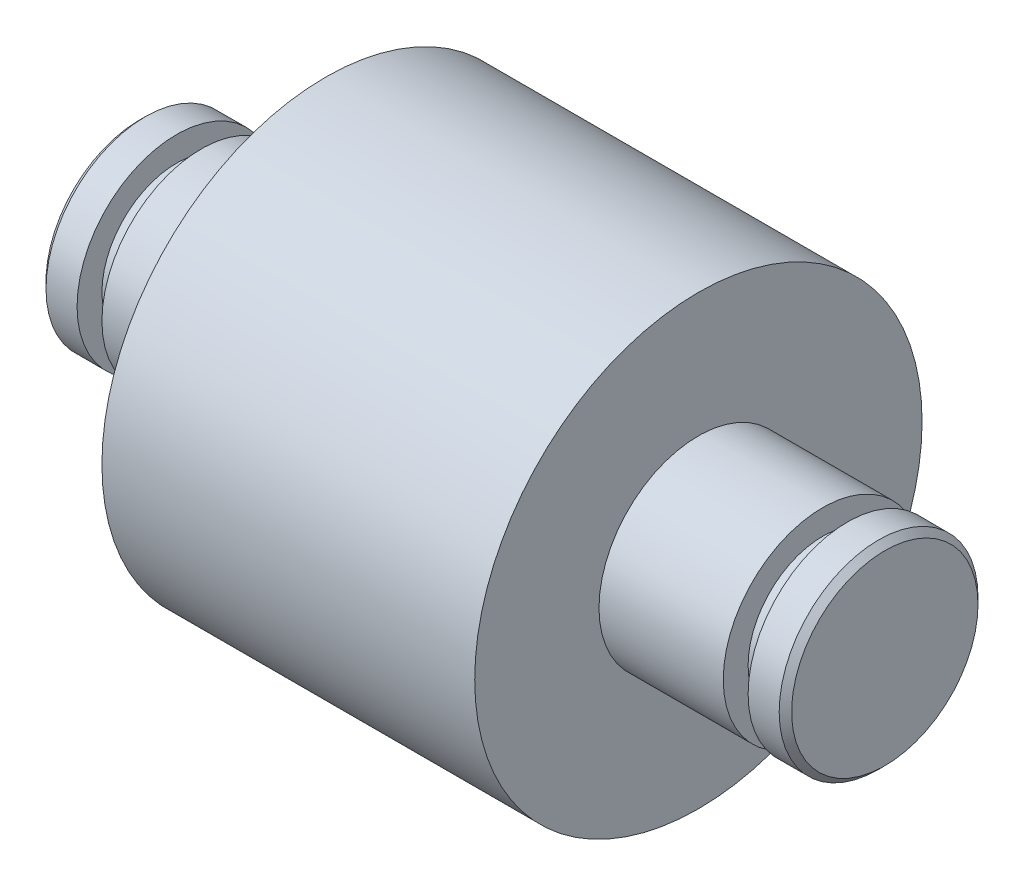
SolidWorks part; units mm, degrees
ref_plane "Front Plane" through (0, 0, 0) normal (0, 0, 1) x (1, 0, 0)
ref_plane "Top Plane" through (0, 0, 0) normal (0, 1, 0) x (1, 0, 0)
ref_plane "Right Plane" through (0, 0, 0) normal (1, 0, 0) x (0, 0, -1)
sketch "Sketch1" plane through (0, 0, 0) normal (0, 0, 1) x (1, 0, 0)
  line L0 (1000, 0) -> (15, 0) construction
  line L1 (0, -1000) -> (0, -9) construction
  line L2 (-15, 0) -> (15, 0)
  line L5 (-7.5, 9) -> (7.5, 9)
  line L7 (-15, 0) -> (15, 0)
  line L11 (12.5, 4) -> (7.5, 4)
  line L17 (13.5, 3) -> (12.5, 3)
  line L19 (-7.5, 9) -> (-7.5, 4)
  line L20 (-13.5, 4) -> (-13.5, 3)
  line L23 (15, 4) -> (13.5, 4)
  line L25 (-12.5, 4) -> (-12.5, 3)
  line L26 (15, 0) -> (-9068.5518, 0) construction
  line L29 (-12.5, 4) -> (-7.5, 4)
  line L35 (-15, 4) -> (-13.5, 4)
  line L39 (-13.5, 3) -> (-12.5, 3)
  line L44 (7.5, 9) -> (7.5, 4)
  line L45 (12.5, 4) -> (12.5, 3)
  line L46 (13.5, 4) -> (13.5, 3)
  line L47 (0, 9) -> (0, 9068.5518) construction
  line L49 (-15, 4) -> (-15, 0)
  line L50 (15, 4) -> (15, 0)
  dimension "D1" = 13.5
  dimension "D2" = 15
  dimension "D3" = 15
  dimension "D4" = 3
  dimension "D9" = 5
revolve "Revolve4" add sketch "Sketch1" angle 360 about L7
chamfer "Chamfer1" distance 0.25 angle 45 2 edges at (-15, 0, 4) (15, 0, 4)
